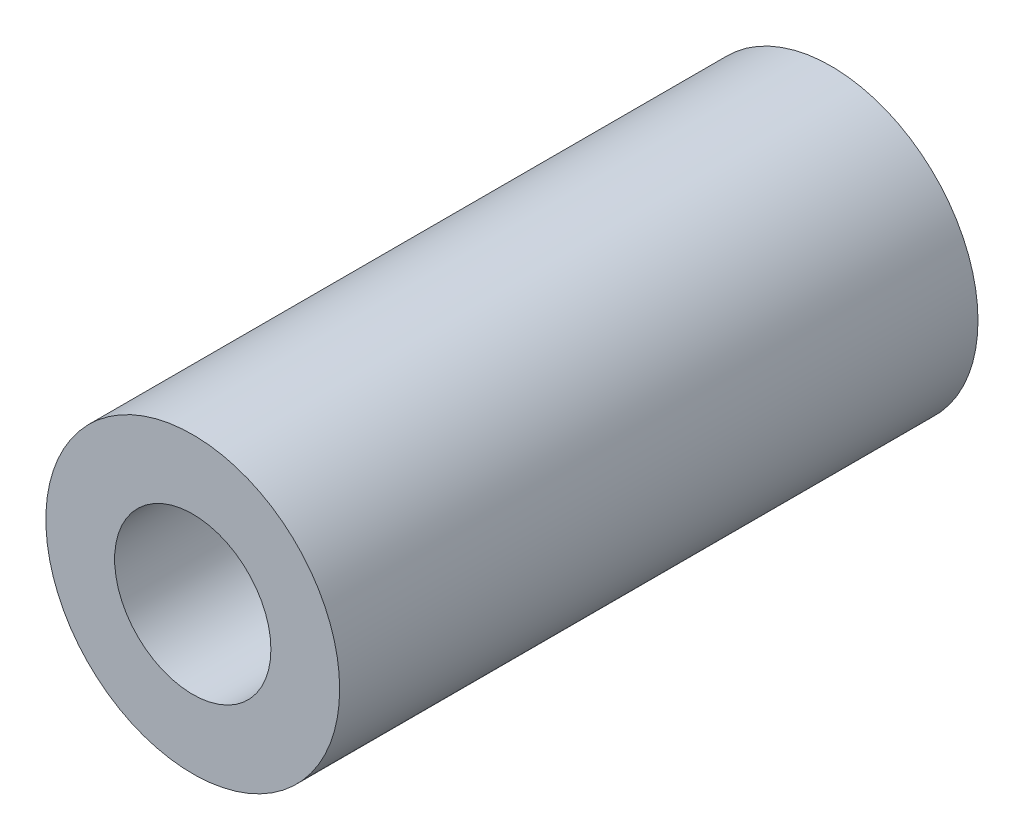
SolidWorks part; units mm, degrees
material "6061-T6 (SS)"
ref_plane "Front Plane" through (0, 0, 0) normal (0, 0, 1) x (1, 0, 0)
ref_plane "Top Plane" through (0, 0, 0) normal (0, 1, 0) x (1, 0, 0)
ref_plane "Right Plane" through (0, 0, 0) normal (1, 0, 0) x (0, 0, -1)
sketch "Sketch1" plane through (0, 0, 0) normal (1, 0, 0) x (0, 0, -1)
  line L0 (0, 0) -> (0, 3.3782) construction
  line L1 (0, 0) -> (6.8636, 0) construction
  line L2 (0, 3.3782) -> (0, 6.35)
  line L3 (0, 6.35) -> (27.5923, 6.35)
  line L4 (27.5923, 6.35) -> (27.5923, 4.6736)
  line L5 (27.5923, 4.6736) -> (28.1003, 4.6736)
  line L6 (28.1003, 4.6736) -> (28.1003, 3.3782)
  line L7 (28.1003, 3.3782) -> (0, 3.3782)
  point P6 (28.1003, 4.0259)
  dimension "D1" = 6.7564
  dimension "D2" = 6.35
  dimension "D3" = 4.6736
  dimension "D4" = 28.1003
  dimension "D5" = 0.508
revolve "Revolve1" add sketch "Sketch1" angle 360 about L1
